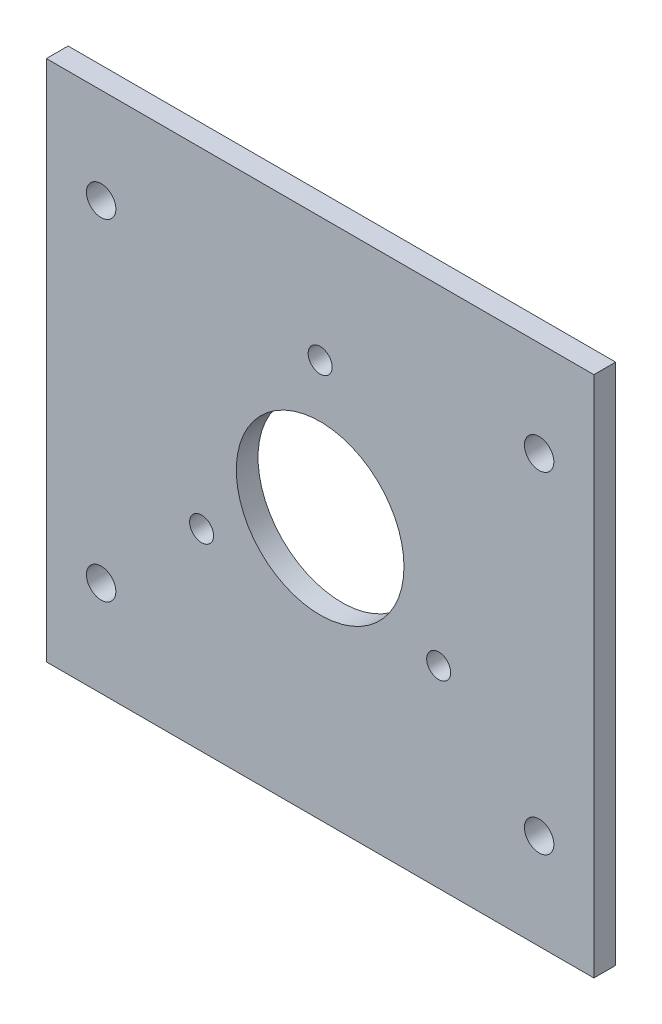
SolidWorks part; units mm, degrees
ref_plane "Front Plane" through (0, 0, 0) normal (0, 0, 1) x (1, 0, 0)
ref_plane "Top Plane" through (0, 0, 0) normal (0, 1, 0) x (1, 0, 0)
ref_plane "Right Plane" through (0, 0, 0) normal (1, 0, 0) x (0, 0, -1)
sketch "Sketch1" plane through (0, 0, 0) normal (0, 0, 1) x (1, 0, 0)
  line L0 (0, 38.175) -> (0, -38.175) construction
  line L1 (-40, -38.175) -> (40, -38.175)
  line L2 (-40, -38.175) -> (-40, 38.175)
  line L3 (-40, 38.175) -> (40, 38.175)
  line L4 (40, -38.175) -> (40, 38.175)
  line L5 (-40, -38.175) -> (40, 38.175) construction
  line L6 (-40, 38.175) -> (40, -38.175) construction
  line L7 (-40, 0) -> (40, 0) construction
  circle A10 centre (0, 0) radius 20 construction
  circle A11 centre (0, 20) radius 1.75
  circle A14 centre (0, 0) radius 12.25
  circle A15 centre (0, 0) radius 33.35 construction
  circle A16 centre (17.3205, -10) radius 1.75
  circle A17 centre (-17.3205, -10) radius 1.75
  circle A18 centre (-32, 24.2) radius 2.15
  circle A19 centre (32, 24.2) radius 2.15
  circle A20 centre (32, -24.2) radius 2.15
  circle A21 centre (-32, -24.2) radius 2.15
  point P0 (0, 0)
  point P17 (0, 0)
  point P52 (0, 0)
  dimension "D4" = 3
  dimension "D6" = 8
  dimension "D7" = 40
  dimension "D9" = 3.5
  dimension "D11" = 24.5
  dimension "D12" = 66.7
  dimension "D5" = 4.3
  dimension "D1" = 76.35
  dimension "D2" = 80
  dimension "D3" = 20
  dimension "D8" = 13.975
extrude "Boss-Extrude1" add sketch "Sketch1" along normal blind 3.175
